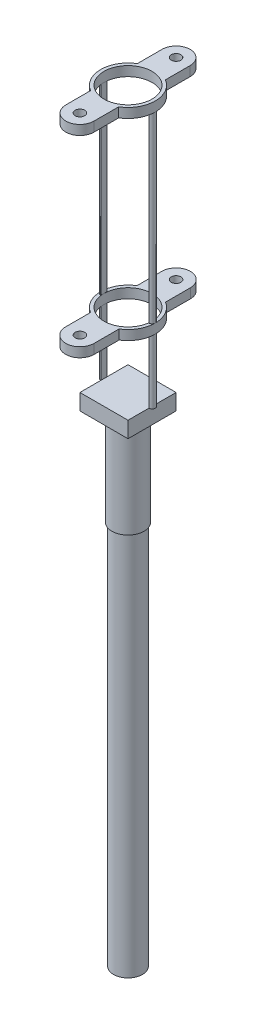
SolidWorks part; units mm, degrees
ref_plane "Front Plane" through (0, 0, 0) normal (0, 0, 1) x (1, 0, 0)
ref_plane "Top Plane" through (0, 0, 0) normal (0, 1, 0) x (1, 0, 0)
ref_plane "Right Plane" through (0, 0, 0) normal (1, 0, 0) x (0, 0, -1)
sketch "Sketch1" plane through (0, 0, 0) normal (0, 1, 0) x (1, 0, 0)
  circle A0 centre (0, 0) radius 5
  dimension "D1" = 10
extrude "Boss-Extrude2" add sketch "Sketch1" along normal blind 40
sketch "Sketch2" plane through (0, 0, 0) normal (0, 1, 0) x (1, 0, 0)
  circle A0 centre (0, 0) radius 5
  circle A1 centre (0, 0) radius 4.5
  dimension "D1" = 10
  dimension "D2" = 9
extrude "Cut-Extrude1" cut sketch "Sketch2" along normal blind 10
ref_plane "Plane1" through (0, 40, 0) normal (0, 1, 0) x (1, 0, 0)
sketch "Sketch3" plane through (0, 40, 0) normal (0, 1, 0) x (1, 0, 0)
  line L1 (-7.5, -7.5) -> (7.5, -7.5)
  line L2 (-7.5, -7.5) -> (-7.5, 7.5)
  line L3 (-7.5, 7.5) -> (7.5, 7.5)
  line L4 (7.5, -7.5) -> (7.5, 7.5)
  line L5 (-7.5, -7.5) -> (7.5, 7.5) construction
  line L6 (-7.5, 7.5) -> (7.5, -7.5) construction
  point P0 (0, 0)
  dimension "D1" = 15
  dimension "D2" = 15
extrude "Boss-Extrude3" add sketch "Sketch3" along normal blind 5
ref_plane "Plane2" through (0, 45, 0) normal (0, 1, 0) x (1, 0, 0)
sketch "Sketch4" plane through (0, 45, 0) normal (0, 1, 0) x (1, 0, 0)
  line L0 (-7.5, 7.5) -> (-7.5, -7.5) construction
  line L1 (7.5, -7.5) -> (7.5, 7.5) construction
  line L2 (-7.5, 1) -> (-7.5, -1)
  line L3 (7.5, 1) -> (7.5, -1)
  circle A0 centre (-7.5, 0) radius 1
  circle A1 centre (7.5, 0) radius 1
  dimension "D1" = 2
  dimension "D2" = 2
extrude "Boss-Extrude4" add sketch "Sketch4" along normal blind 80 separate body contours L2 A0 | L3 A1
ref_plane "Plane3" through (0, 65, 0) normal (0, 1, 0) x (1, 0, 0)
sketch "Sketch5" plane through (0, 65, 0) normal (0, 1, 0) x (1, 0, 0)
  circle A0 centre (0, 0) radius 8.5
  circle A1 centre (0, 0) radius 7.5
  dimension "D1" = 17
extrude "Boss-Extrude5" add sketch "Sketch5" along normal blind 3
sketch "Sketch6" plane through (0, 65, 0) normal (0, 1, 0) x (1, 0, 0)
  line L0 (0, -15.0003) -> (0, 15.0003) construction
  line L1 (-4.4517, -15.0003) -> (-4.4517, 15.0003)
  line L2 (4.4517, -15.0003) -> (4.4517, 15.0003)
  arc A0 (-4.4517, -15.0003) -> (4.4517, -15.0003) centre (0, -15.0003) ccw
  arc A1 (4.4517, 15.0003) -> (-4.4517, 15.0003) centre (0, 15.0003) ccw
  circle A2 centre (0, 0) radius 8.5
  circle A3 centre (0, 0) radius 7.5
  circle A4 centre (0, -15.0003) radius 1.5
  circle A5 centre (0, 15.0003) radius 1.5
  point P2 (0, 0)
  dimension "D1" = 4.4517
  dimension "D3" = 15
  dimension "D4" = 3
  dimension "D5" = 3
  dimension "D2" = 15.0003
extrude "Boss-Extrude6" add sketch "Sketch6" along normal blind 3
sketch "Sketch7" plane through (0, 0, 0) normal (0, 1, 0) x (1, 0, 0)
  circle A0 centre (0, 0) radius 4.5
  dimension "D1" = 9
extrude "Boss-Extrude7" add sketch "Sketch7" against normal blind 110
ref_plane "Plane5" through (0, 125, 0) normal (0, 1, 0) x (1, 0, 0)
sketch "Sketch8" plane through (0, 125, 0) normal (0, 1, 0) x (1, 0, 0)
  line L0 (0, -15.0003) -> (0, 15.0003) construction
  line L1 (-4.3814, -15.0003) -> (-4.3814, 15.0003)
  line L2 (4.3814, -15.0003) -> (4.3814, 15.0003)
  circle A0 centre (0, 0) radius 7.5
  circle A1 centre (0, 0) radius 8.5
  arc A2 (-4.3814, -15.0003) -> (4.3814, -15.0003) centre (0, -15.0003) ccw
  arc A3 (4.3814, 15.0003) -> (-4.3814, 15.0003) centre (0, 15.0003) ccw
  point P6 (0, 0)
  dimension "D1" = 4.3814
  dimension "D2" = 17
  dimension "D3" = 15
extrude "Boss-Extrude8" add sketch "Sketch8" along normal blind 3
sketch "Sketch10" plane through (0, 128, 0) normal (0, 1, 0) x (1, 0, 0)
  line L0 (0, 0) -> (20.9639, 0) construction
  circle A0 centre (0, -15.0003) radius 1.5
  circle A1 centre (0, 15.0003) radius 1.5
  dimension "D2" = 3
extrude "Cut-Extrude2" cut sketch "Sketch10" against normal blind 3
